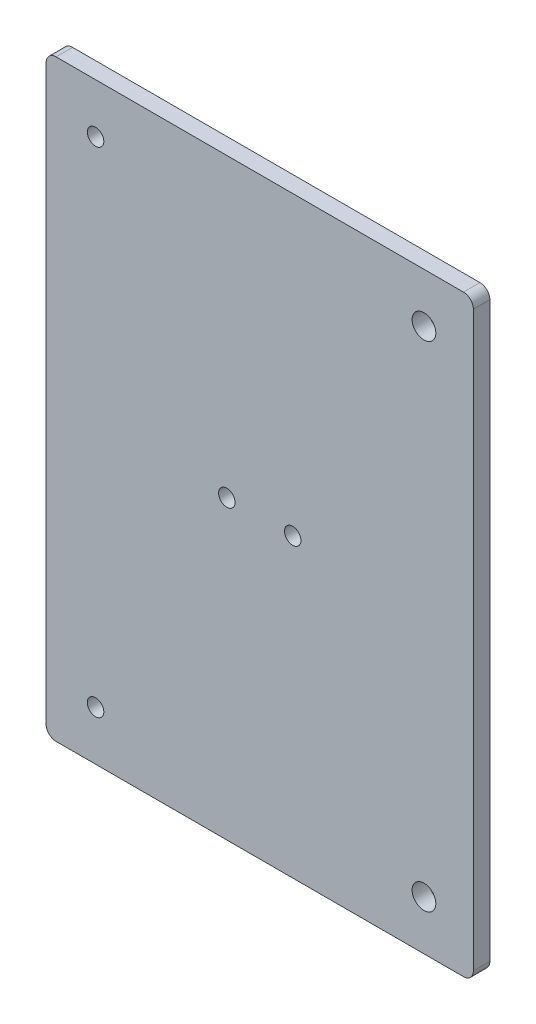
SolidWorks part; units mm, degrees
ref_plane "Płaszczyzna przednia" through (0, 0, 0) normal (0, 0, 1) x (1, 0, 0)
ref_plane "Płaszczyzna górna" through (0, 0, 0) normal (0, 1, 0) x (1, 0, 0)
ref_plane "Płaszczyzna prawa" through (0, 0, 0) normal (1, 0, 0) x (0, 0, -1)
sketch "Sketch1" plane through (0, 0, 0) normal (0, 0, 1) x (1, 0, 0)
  line L0 (64.85, -11.9796) -> (64.85, 45.4278) construction
  line L1 (0, 0) -> (129.7, 0)
  line L2 (0, 0) -> (0, 180)
  line L3 (0, 180) -> (129.7, 180)
  line L4 (129.7, 0) -> (129.7, 180)
  line L5 (54.85, 90) -> (74.85, 90) construction
  line L6 (166.9359, 130) -> (-13.2189, 130) construction
  line L7 (166.9359, 50) -> (-17.016, 50) construction
  line L8 (-17.016, 140) -> (166.9359, 140) construction
  line L9 (-13.2189, 40) -> (174.7412, 40) construction
  line L10 (64.85, 180) -> (64.85, 0) construction
  circle A0 centre (15, 15) radius 2.5
  circle A1 centre (15, 165) radius 2.5
  circle A2 centre (114.7, 165) radius 3.6
  circle A3 centre (114.7, 15) radius 3.6
  circle A10 centre (74.85, 90) radius 2.5
  circle A11 centre (54.85, 90) radius 2.5
  point P18 (64.85, 0)
  point P23 (64.85, 90)
  point P24 (50.6839, 90)
  point P32 (75.6839, 90)
  point P38 (0, 90)
  dimension "D1" = 5
  dimension "D2" = 5
  dimension "D3" = 7.2
  dimension "D4" = 7.2
  dimension "D10" = 5
  dimension "D5" = 99.7
  dimension "D6" = 150
  dimension "D7" = 15
  dimension "D8" = 15
  dimension "D9" = 15
  dimension "D11" = 40
  dimension "D12" = 40
  dimension "D13" = 10
  dimension "D14" = 10
  dimension "D15" = 20
extrude "Boss-Extrude1" add sketch "Sketch1" along normal blind 5
fillet "Fillet1" radius 3 4 edges at (0, 0, 2.5) (129.7, 0, 2.5) (0, 180, 2.5) (129.7, 180, 2.5)
